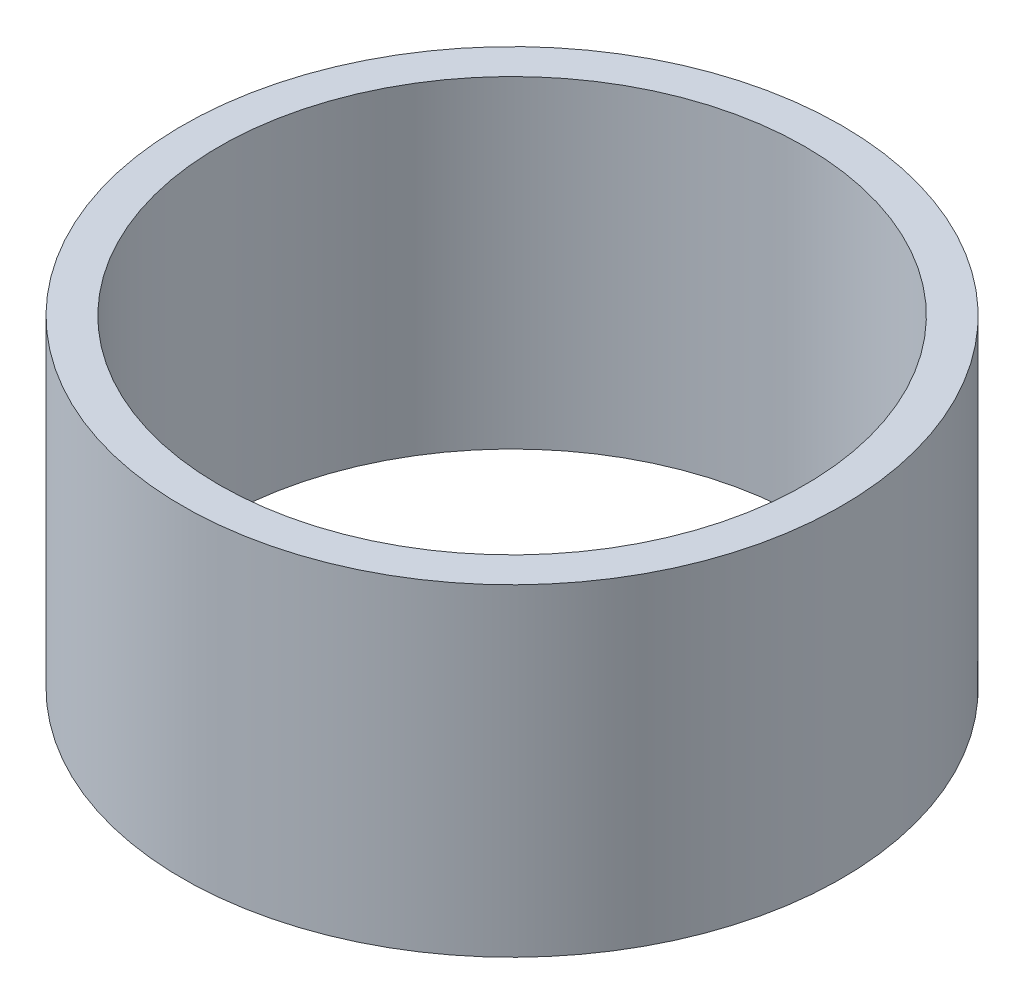
SolidWorks part; units mm, degrees
material "6061-T6 (SS)"
ref_plane "Front Plane" through (0, 0, 0) normal (0, 0, 1) x (1, 0, 0)
ref_plane "Top Plane" through (0, 0, 0) normal (0, 1, 0) x (1, 0, 0)
ref_plane "Right Plane" through (0, 0, 0) normal (1, 0, 0) x (0, 0, -1)
sketch "Sketch1" plane through (0, 0, 0) normal (1, 0, 0) x (0, 0, -1)
  line L0 (0, 0) -> (0, 23.9672) construction
  line L2 (12.7, 0) -> (14.2875, 0)
  line L3 (12.7, 0) -> (12.7, 13.985)
  line L4 (12.7, 13.985) -> (14.2875, 13.985)
  line L5 (14.2875, 0) -> (14.2875, 13.985)
  dimension "D1" = 25.4
  dimension "D2" = 28.575
  dimension "D3" = 13.985
revolve "Revolve1" add sketch "Sketch1" angle 360 about L0
